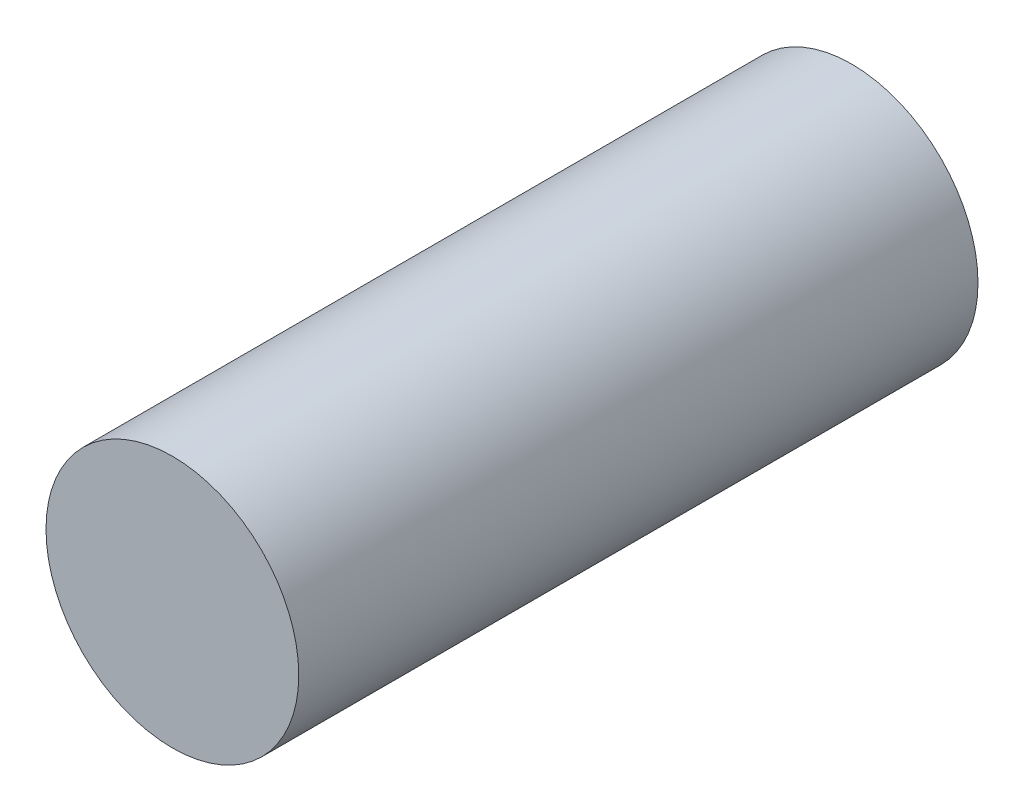
SolidWorks part; units mm, degrees
material "Cast Alloy Steel"
ref_plane "Front Plane" through (0, 0, 0) normal (0, 0, 1) x (1, 0, 0)
ref_plane "Top Plane" through (0, 0, 0) normal (0, 1, 0) x (1, 0, 0)
ref_plane "Right Plane" through (0, 0, 0) normal (1, 0, 0) x (0, 0, -1)
sketch "Sketch1" plane through (0, 0, 0) normal (0, 0, 1) x (1, 0, 0)
  circle A0 centre (0, 0) radius 4
  dimension "D1" = 8
extrude "Boss-Extrude1" add sketch "Sketch1" along normal blind 21.5
sketch "Sketch2" plane through (0, 0, 21.5) normal (0, 0, 1) x (1, 0, 0)
  line L1 (-5.25, 1.6259) -> (-2.75, 1.6259)
  line L2 (-5.25, 1.6259) -> (-5.25, -1.6259)
  line L3 (-5.25, -1.6259) -> (-2.75, -1.6259)
  line L4 (-2.75, 1.6259) -> (-2.75, -1.6259)
  line L5 (-5.25, 1.6259) -> (-2.75, -1.6259) construction
  line L6 (-5.25, -1.6259) -> (-2.75, 1.6259) construction
  circle A0 centre (0, 0) radius 4 construction
  point P0 (-4, 0)
  dimension "D1" = 2.5
extrude "Cut-Extrude1" cut sketch "Sketch2" against normal blind 15 from offset 3 offset against normal yes
fillet "Fillet2" radius 1.5 2 edges at (-3.2023, -1.6259, 3.5) (-3.2023, 1.6259, 3.5)
fillet "Fillet3" radius 1.5 2 edges at (-3.2023, 1.6259, 18.5) (-3.2023, -1.6259, 18.5)
